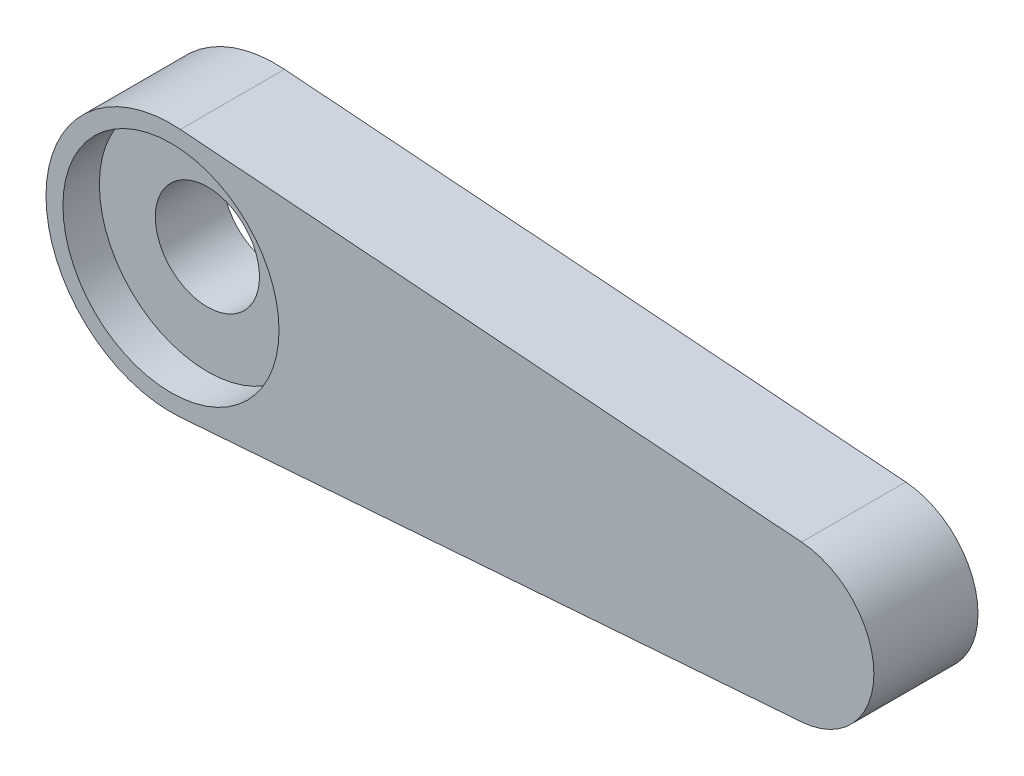
SolidWorks part; units mm, degrees
ref_plane "前视基准面" through (0, 0, 0) normal (0, 0, 1) x (1, 0, 0)
ref_plane "上视基准面" through (0, 0, 0) normal (0, 1, 0) x (1, 0, 0)
ref_plane "右视基准面" through (0, 0, 0) normal (1, 0, 0) x (0, 0, -1)
sketch "草图1" plane through (0, 0, 0) normal (0, 0, 1) x (1, 0, 0)
  line L0 (0, 0) -> (60, 0) construction
  line L1 (0.9, -11.9662) -> (60.5625, -7.4789)
  line L2 (0.9, 11.9662) -> (60.5625, 7.4789)
  arc A0 (60.5625, 7.4789) -> (60.5625, -7.4789) centre (60, 0) cw
  arc A1 (0.9, -11.9662) -> (0.9, 11.9662) centre (0, 0) cw
  dimension "D2" = 12
  dimension "D3" = 7.5
  dimension "D1" = 60
extrude "凸台-拉伸1" add sketch "草图1" along normal blind 10 contours A1 L2 A0 L1
sketch "草图2" plane through (0, 0, 10) normal (0, 0, 1) x (1, 0, 0)
  circle A0 centre (0, 0) radius 10.375
  dimension "D1" = 20.75
extrude "切除-拉伸1" cut sketch "草图2" against normal blind 3.5
sketch "草图3" plane through (0, 0, 0) normal (0, 0, -1) x (-1, 0, 0)
  circle A0 centre (0, 0) radius 5
  dimension "D1" = 10
extrude "切除-拉伸2" cut sketch "草图3" against normal through all
